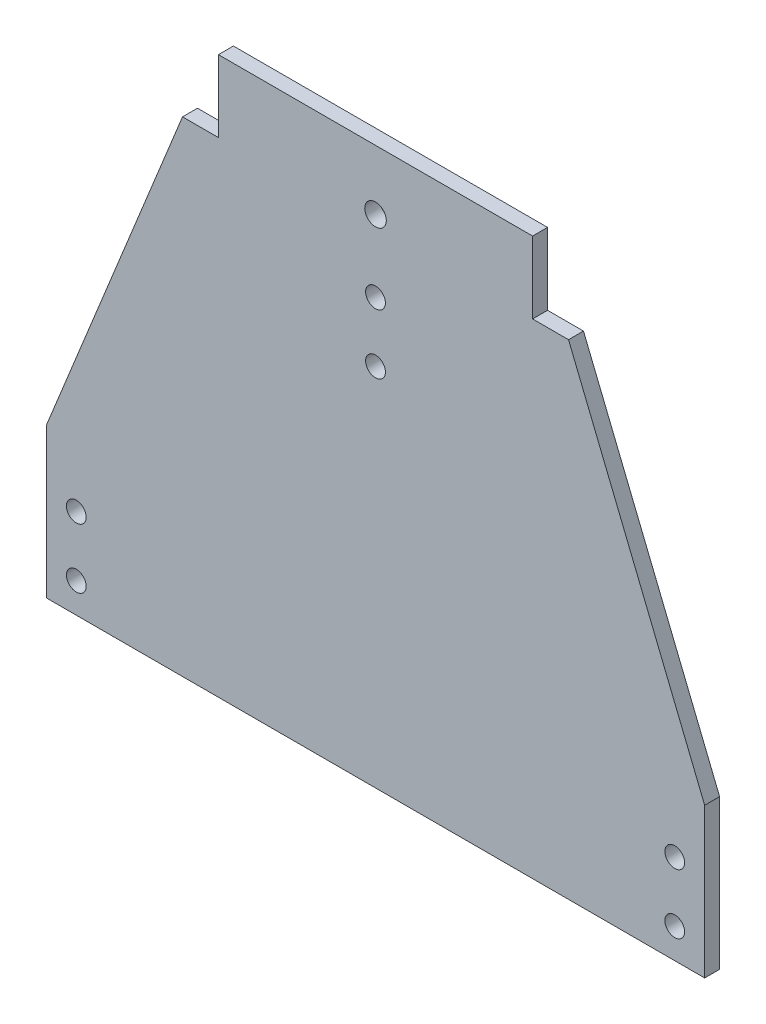
SolidWorks part; units mm, degrees
material "ABS"
ref_plane "Front Plane" through (0, 0, 0) normal (0, 0, 1) x (1, 0, 0)
ref_plane "Top Plane" through (0, 0, 0) normal (0, 1, 0) x (1, 0, 0)
ref_plane "Right Plane" through (0, 0, 0) normal (1, 0, 0) x (0, 0, -1)
sketch "Sketch1" plane through (0, 0, 0) normal (0, 0, 1) x (1, 0, 0)
  line L0 (0, 0) -> (26.25, 0)
  line L1 (26.25, 0) -> (26.25, -12)
  line L3 (55, -68) -> (55, -83)
  line L4 (55, -83) -> (0, -83)
  line L5 (0, -83) -> (0, 0)
  line L6 (26.25, -12) -> (32.25, -12)
  line L7 (32.25, -12) -> (55, -68)
  line L8 (0, -3.5) -> (22.75, -3.5)
  line L9 (0, -83) -> (55, -83)
  line L10 (0, -83) -> (0, -93)
  line L11 (0, -93) -> (55, -93)
  line L12 (55, -83) -> (55, -93)
  line L13 (55, -83) -> (62, -83)
  line L14 (55, -83) -> (55, -73)
  line L15 (55, -73) -> (59, -73)
  line L16 (62, -83) -> (62, -76)
  line L17 (55, -83) -> (62, -83)
  line L18 (55, -83) -> (55, -93)
  line L19 (55, -93) -> (59, -93)
  line L20 (62, -83) -> (62, -90)
  line L21 (55, -83) -> (44.5, -83)
  line L22 (55, -83) -> (55, -77.5)
  line L23 (55, -77.5) -> (44.5, -77.5)
  line L24 (44.5, -83) -> (44.5, -77.5)
  line L25 (44.5, -83) -> (55, -83)
  line L26 (44.5, -83) -> (44.5, -87.5)
  line L27 (44.5, -87.5) -> (55, -87.5)
  line L28 (55, -83) -> (55, -87.5)
  line L29 (22.75, -3.5) -> (22.75, -15.5)
  line L30 (22.75, -15.5) -> (29.8941, -15.5)
  line L31 (29.8941, -15.5) -> (51.5, -68.6838)
  line L32 (51.5, -68.6838) -> (51.5, -83)
  line L33 (51.5, -83) -> (51.5, -93)
  line L34 (0, -5.5) -> (20.75, -5.5)
  line L35 (20.75, -5.5) -> (20.75, -17.5)
  line L36 (20.75, -17.5) -> (28.5478, -17.5)
  line L37 (28.5478, -17.5) -> (49.5, -69.0745)
  line L38 (49.5, -69.0745) -> (49.5, -83)
  line L39 (55, -75.5) -> (42.5, -75.5)
  line L40 (42.5, -83) -> (42.5, -75.5)
  line L41 (42.5, -83) -> (42.5, -89.5)
  line L42 (42.5, -89.5) -> (55, -89.5)
  line L43 (49.5, -83) -> (49.5, -93)
  line L44 (22.75, -15.5) -> (22.75, -17.5)
  circle A0 centre (58.5, -78) radius 1.7
  circle A1 centre (58.5, -88) radius 1.7
  arc A2 (59, -93) -> (62, -90) centre (59, -90) ccw
  arc A3 (59, -73) -> (62, -76) centre (59, -76) cw
  point P24 (62, -73)
  dimension "D10" = 3.4
  dimension "D11" = 3.4
  dimension "D15" = 3
  dimension "D16" = 3
  dimension "D1" = 26.25
  dimension "D2" = 12
  dimension "D3" = 55
  dimension "D4" = 71
  dimension "D5" = 6
  dimension "D6" = 15
  dimension "D7" = 10
  dimension "D8" = 7
  dimension "D9" = 10
  dimension "D12" = 3.5
  dimension "D13" = 5
  dimension "D14" = 5
  dimension "D17" = 5.5
  dimension "D18" = 10.5
  dimension "D19" = 4.5
  dimension "D20" = 3.5
  dimension "D21" = 2
  dimension "D22" = 2
extrude "Boss-Extrude1" add sketch "Sketch1" along normal blind 2.5
mirror "Mirror1" about plane through (0, 0, 0) normal (1, 0, 0) of "Boss-Extrude1"
hole_wizard "M3 Clearance Hole1" positions "Sketch2" profile "Sketch3" hole size "M3" standard "ISO" end condition through all
sketch "Sketch2" plane through (0, 0, 0) normal (0, 0, -1) x (-1, 0, 0)
  line L0 (26.25, 0) -> (-26.25, 0) construction
  point P0 (0, -10)
  dimension "D1" = 10
sketch "Sketch3" plane through (0, -10, 0) normal (1, 0, 0) x (0, 1, 0)
  line L0 (0, 0) -> (0, 2.5)
  line L1 (0, 2.5) -> (1.8, 2.5)
  line L2 (1.8, 2.5) -> (1.8, 0)
  line L5 (1.8, 0) -> (0, 0)
  line L11 (0, -6.35) -> (0, 107.95) construction
  dimension "Thru Hole Dia." = 3.6
  dimension "Thru Hole Depth" = 2.5
sketch "Sketch4" plane through (0, 0, 0) normal (1, 0, 0) x (0, 0, -1)
  line L0 (0, -85) -> (5.2002, -91.3431)
  line L1 (0, -11.8) -> (0, -8.2) construction
  line L2 (0, -85) -> (0, -93)
  line L3 (0, -93) -> (0.1502, -93)
  circle A0 centre (2.9962, -93.15) radius 1.1
  circle A1 centre (2.9962, -93.15) radius 2.85
  dimension "D1" = 2.2
  dimension "D2" = 5.7
  dimension "D3" = 0.15
  dimension "D4" = 2.9962
  dimension "D5" = 8
extrude "Boss-Extrude3" add sketch "Sketch4" along normal mid plane 90 contours A1 L0 L2 L3 | A1 A0
sketch "Sketch5" plane through (0, 0, 0) normal (0, 0, -1) x (-1, 0, 0)
  line L0 (-45, -85) -> (45, -85) construction
  line L1 (-45, -85) -> (-27.4, -85)
  line L2 (-45, -85) -> (-45, -119.3219)
  line L3 (-45, -119.3219) -> (-27.4, -119.3219)
  line L4 (-27.4, -85) -> (-27.4, -119.3219)
  line L5 (-26.9, -85) -> (-9.3, -85)
  line L6 (-26.9, -85) -> (-26.9, -119.3219)
  line L7 (-26.9, -119.3219) -> (-9.3, -119.3219)
  line L8 (-9.3, -85) -> (-9.3, -119.3219)
  line L9 (-45, -85) -> (45, -85)
  line L10 (-8.8, -85) -> (8.8, -85)
  line L11 (-8.8, -85) -> (-8.8, -119.3219)
  line L12 (-8.8, -119.3219) -> (8.8, -119.3219)
  line L13 (8.8, -85) -> (8.8, -119.3219)
  line L14 (9.3, -85) -> (26.9, -85)
  line L15 (9.3, -85) -> (9.3, -119.3219)
  line L16 (9.3, -119.3219) -> (26.9, -119.3219)
  line L17 (26.9, -85) -> (26.9, -119.3219)
  line L18 (45, -85) -> (27.4, -85)
  line L19 (45, -85) -> (45, -119.3219)
  line L20 (45, -119.3219) -> (27.4, -119.3219)
  line L21 (27.4, -85) -> (27.4, -119.3219)
  line L22 (45, -119.3219) -> (-45, -119.3219)
  line M14 (-45, -85) -> (45, -85)
  dimension "D1" = 17.6
  dimension "D2" = 0.5
  dimension "D3" = 17.6
  dimension "D4" = 17.6
  dimension "D5" = 17.6
  dimension "D6" = 17.6
  dimension "D7" = 0.5
  dimension "D8" = 0.5
  dimension "D9" = 0.5
extrude "Cut-Extrude1" cut sketch "Sketch5" along normal blind 23 contours L8 L6 L7 M14 | L17 L15 L16 M14 | L22 L6 L4 M14 | L22 L11 L8 M14 | L22 L15 L13 M14 | L22 L21 L17 M14
sketch "Sketch6" plane through (0, 0, 0) normal (0, 0, -1) x (-1, 0, 0)
  line L0 (-55, -68) -> (-55, -93) construction
  line L1 (55, -68) -> (55, -93) construction
  circle A0 centre (-50, -88) radius 1.65
  circle A1 centre (-50, -78) radius 1.65
  circle A2 centre (50, -88) radius 1.65
  circle A3 centre (50, -78) radius 1.65
  circle A4 centre (0, -10) radius 1.8 construction
  dimension "D3" = 3.3
  dimension "D4" = 68
  dimension "D1" = 5
  dimension "D2" = 5
  dimension "D5" = 10
extrude "Cut-Extrude2" cut sketch "Sketch6" against normal blind 10
sketch "Sketch7" plane through (0, 0, 0) normal (0, 0, -1) x (-1, 0, 0)
  line L0 (26.25, -12) -> (32.25, -12) construction
  circle A0 centre (0, -22) radius 1.65
  circle A1 centre (0, -32) radius 1.65
  point P4 (0, 0)
  dimension "D1" = 3.3
  dimension "D2" = 10
  dimension "D3" = 10
extrude "Cut-Extrude3" cut sketch "Sketch7" against normal blind 10
equation "\"D3@Sketch5\"=\"D1@Sketch5\""
equation "\"D4@Sketch5\"=\"D1@Sketch5\""
equation "\"D5@Sketch5\"=\"D1@Sketch5\""
equation "\"D6@Sketch5\"=\"D1@Sketch5\""
equation "\"D7@Sketch5\"=\"D2@Sketch5\""
equation "\"D8@Sketch5\"=\"D2@Sketch5\""
